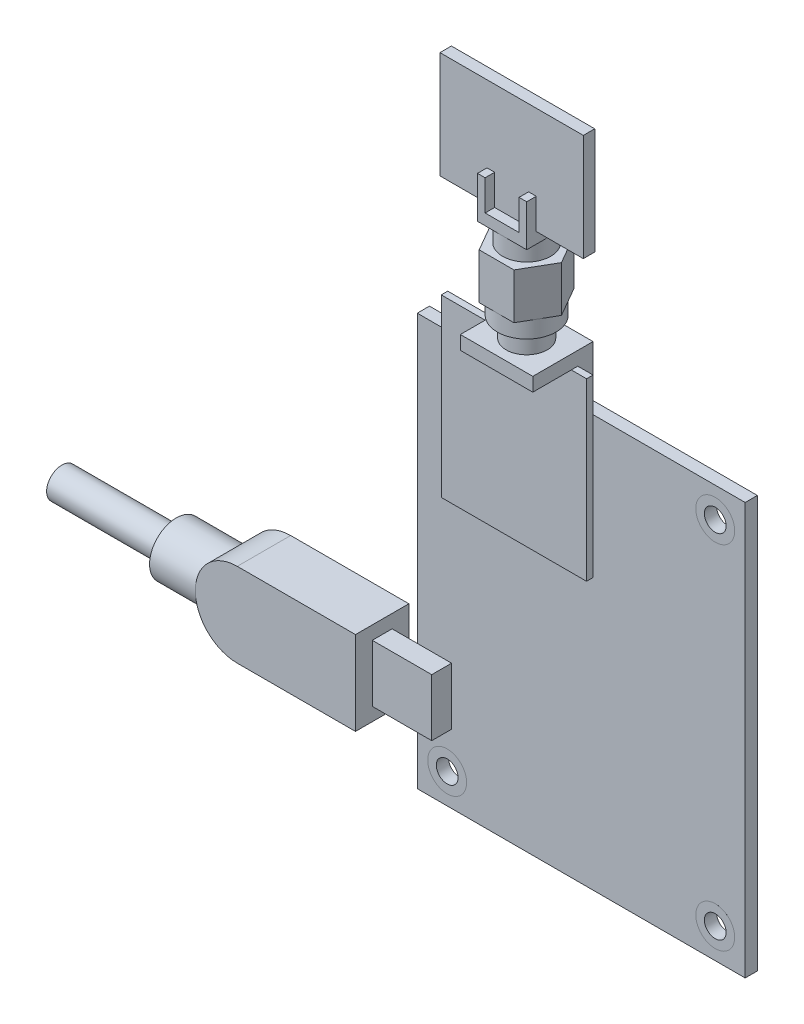
SolidWorks part; units mm, degrees
ref_plane "Front Plane" through (0, 0, 0) normal (0, 0, 1) x (1, 0, 0)
ref_plane "Top Plane" through (0, 0, 0) normal (0, 1, 0) x (1, 0, 0)
ref_plane "Right Plane" through (0, 0, 0) normal (1, 0, 0) x (0, 0, -1)
sketch "Sketch1" plane through (0, 0, 0) normal (0, 0, 1) x (1, 0, 0)
  line L1 (0, 0) -> (19.05, 0)
  line L2 (0, 0) -> (0, 23)
  line L3 (0, 23) -> (19.05, 23)
  line L4 (19.05, 0) -> (19.05, 23)
  dimension "D1" = 19.05
  dimension "D2" = 23
extrude "Blue PCB" add sketch "Sketch1" along normal mid plane 0.85
sketch "Sketch20" plane through (0, 0, -0.425) normal (0, 0, -1) x (-1, 0, 0)
  line L0 (-19.05, 23) -> (0, 23) construction
  line L1 (4, 18.5) -> (-39, 18.5)
  line L2 (4, 18.5) -> (4, -35.5)
  line L3 (4, -35.5) -> (-39, -35.5)
  line L4 (-39, 18.5) -> (-39, -35.5)
  line L5 (0, 23) -> (0, 0) construction
  dimension "D1" = 43
  dimension "D2" = 54
  dimension "D3" = 4.5
  dimension "D4" = 4
extrude "Green PCB" add sketch "Sketch20" along normal blind 1.6
ref_plane "Plane3" through (0, 0, -1.225) normal (0, 0, 1) x (1, 0, 0)
sketch "Sketch21" plane through (0, 0, -0.425) normal (0, 0, 1) x (1, 0, 0)
  line L0 (39, 18.5) -> (39, -35.5) construction
  line L1 (35.075, 14.575) -> (-0.075, 14.575) construction
  line L2 (35.075, 14.575) -> (35.075, -31.575) construction
  line L3 (35.075, -31.575) -> (-0.075, -31.575) construction
  line L4 (-0.075, 14.575) -> (-0.075, -31.575) construction
  line L5 (19.05, 18.5) -> (39, 18.5) construction
  line L6 (39, -35.5) -> (-4, -35.5) construction
  line L7 (-4, -35.5) -> (-4, 18.5) construction
  circle A0 centre (35.075, 14.575) radius 1.425
  circle A1 centre (35.075, -31.575) radius 1.425
  circle A2 centre (-0.075, -31.575) radius 1.425
  point P6 (33.5564, -31.4187)
  dimension "D1" = 2.85
  dimension "D2" = 3.925
  dimension "D3" = 3.925
  dimension "D4" = 3.925
  dimension "D5" = 3.925
extrude "Mounting Holes" cut sketch "Sketch21" against normal through all
sketch "Sketch22" plane through (0, 0, -1.225) normal (0, 0, 1) x (1, 0, 0)
  circle A0 centre (35.075, 14.575) radius 2.55
  circle A1 centre (35.075, -31.575) radius 2.55
  circle A2 centre (-0.075, -31.575) radius 2.55
  circle A3 centre (-0.075, -31.575) radius 1.425
  circle A4 centre (35.075, -31.575) radius 1.425
  circle A5 centre (35.075, 14.575) radius 1.425
  circle A6 centre (35.075, 14.575) radius 1.425 construction
  circle A7 centre (35.075, -31.575) radius 1.425 construction
  circle A8 centre (-0.075, -31.575) radius 1.425 construction
  dimension "D1" = 5.1
extrude "Screw Mask" add sketch "Sketch22" along normal offset from surface 0.001 and the other way offset from surface (0.801 mm away) 0.001 up to face at (36.5, 14.575, -0.425) offset beyond the face yes other way up to face at (36.5, 14.575, -2.025)
sketch "Sketch4" plane through (0, 23, 0) normal (0, 1, 0) x (1, 0, 0)
  line L0 (19.05, -0.425) -> (19.05, 0.425) construction
  line L1 (7.55, 2.425) -> (17.05, 2.425)
  line L2 (7.55, 2.425) -> (7.55, -5.475)
  line L3 (7.55, -5.475) -> (17.05, -5.475)
  line L4 (17.05, 2.425) -> (17.05, -5.475)
  line L6 (19.05, 0.425) -> (0, 0.425) construction
  dimension "D1" = 7.9
  dimension "D2" = 9.5
  dimension "D3" = 2
  dimension "D4" = 2
extrude "Antenna1" add sketch "Sketch4" along normal blind 1.8
sketch "Sketch10" plane through (0, 0, -2.425) normal (0, 0, 1) x (1, 0, 0)
  line L1 (7.55, 23) -> (8.8, 23)
  line L2 (7.55, 23) -> (7.55, 18.5)
  line L3 (7.55, 18.5) -> (8.8, 18.5)
  line L4 (8.8, 23) -> (8.8, 18.5)
  line L5 (17.05, 23) -> (15.8, 23)
  line L6 (17.05, 23) -> (17.05, 18.5)
  line L7 (17.05, 18.5) -> (15.8, 18.5)
  line L8 (15.8, 23) -> (15.8, 18.5)
  dimension "D1" = 1.25
  dimension "D2" = 4.5
extrude "Antenna2" add sketch "Sketch10" against normal up to surface (2.85 mm away)
sketch "Sketch5" plane through (0, 24.8, 0) normal (0, 1, 0) x (1, 0, 0)
  line L0 (17.05, 2.425) -> (7.55, -5.475) construction
  circle A0 centre (12.3, -1.525) radius 2.7
  dimension "D1" = 5.4
extrude "Antenna3" add sketch "Sketch5" along normal blind 2.6
sketch "Sketch6" plane through (0, 27.4, 0) normal (0, 1, 0) x (1, 0, 0)
  circle A0 centre (12.3, -1.525) radius 3.85
  dimension "D1" = 7.7
extrude "Antenna4" add sketch "Sketch6" along normal blind 2.25
sketch "Sketch7" plane through (0, 29.65, 0) normal (0, 1, 0) x (1, 0, 0)
  line L0 (7.55, -5.475) -> (17.05, -5.475) construction
  line L1 (10.0195, -5.475) -> (14.5805, -5.475)
  line L2 (14.5805, -5.475) -> (16.8611, -1.525)
  line L3 (16.8611, -1.525) -> (14.5805, 2.425)
  line L4 (14.5805, 2.425) -> (10.0195, 2.425)
  line L5 (10.0195, 2.425) -> (7.7389, -1.525)
  line L6 (7.7389, -1.525) -> (10.0195, -5.475)
  circle A0 centre (12.3, -1.525) radius 3.95 construction
  dimension "D1" = 7.9
extrude "Antenna5" add sketch "Sketch7" along normal blind 6
sketch "Sketch8" plane through (0, 35.65, 0) normal (0, 1, 0) x (1, 0, 0)
  circle A0 centre (12.3, -1.525) radius 3.15
  dimension "D1" = 6.3
extrude "Antenna6" add sketch "Sketch8" along normal blind 2.4
sketch "Sketch9" plane through (0, 38.05, 0) normal (0, 1, 0) x (1, 0, 0)
  line L1 (15.525, 1.7) -> (9.075, 1.7)
  line L2 (15.525, 1.7) -> (15.525, -4.75)
  line L3 (15.525, -4.75) -> (9.075, -4.75)
  line L4 (9.075, 1.7) -> (9.075, -4.75)
  line L5 (15.525, 1.7) -> (9.075, -4.75) construction
  line L6 (15.525, -4.75) -> (9.075, 1.7) construction
  point P0 (12.3, -1.525)
  dimension "D1" = 6.45
  dimension "D2" = 6.45
extrude "Antenna7" add sketch "Sketch9" along normal blind 1.45
sketch "Sketch19" plane through (0, 0, 4.75) normal (0, 0, 1) x (1, 0, 0)
  line L0 (9.075, 39.5) -> (9.075, 38.05) construction
  line L1 (9.075, 39.5) -> (10.075, 39.5)
  line L2 (9.075, 39.5) -> (9.075, 43.5)
  line L3 (9.075, 43.5) -> (10.075, 43.5)
  line L4 (10.075, 39.5) -> (10.075, 43.5)
  line L5 (9.075, 39.5) -> (15.525, 39.5) construction
  line L7 (15.525, 39.5) -> (14.525, 39.5)
  line L8 (15.525, 39.5) -> (15.525, 43.5)
  line L9 (15.525, 43.5) -> (14.525, 43.5)
  line L10 (14.525, 39.5) -> (14.525, 43.5)
  dimension "D1" = 1
  dimension "D2" = 4
extrude "Antenna8" add sketch "Sketch19" against normal blind 1.25
sketch "Sketch11" plane through (0, 39.5, 0) normal (0, 1, 0) x (1, 0, 0)
  line L0 (14.525, -3.5) -> (15.525, -3.5) construction
  line L1 (21.7, -2) -> (2.9, -2)
  line L2 (21.7, -2) -> (21.7, -3.5)
  line L3 (21.7, -3.5) -> (2.9, -3.5)
  line L4 (2.9, -2) -> (2.9, -3.5)
  line L6 (12.3, 1.7) -> (12.3, -4.75) construction
  line L7 (15.525, 1.7) -> (9.075, 1.7) construction
  line L8 (10.075, -4.75) -> (14.525, -4.75) construction
  point P6 (0.3478, -3.5)
  point P7 (12.3, -2)
  dimension "D1" = 18.8
  dimension "D2" = 1.5
extrude "Antenna PCB" add sketch "Sketch11" along normal blind 14
sketch "Sketch14" plane through (0, 0, -0.425) normal (0, 0, -1) x (-1, 0, 0)
  line L1 (-0.5, -19) -> (7.3, -19)
  line L2 (-0.5, -19) -> (-0.5, -26.5)
  line L3 (-0.5, -26.5) -> (7.3, -26.5)
  line L4 (7.3, -19) -> (7.3, -26.5)
  line L5 (-39, -35.5) -> (4, -35.5) construction
  line L7 (4, -35.5) -> (4, 18.5) construction
  dimension "D1" = 7.5
  dimension "D2" = 7.8
  dimension "D3" = 9
  dimension "D4" = 4.5
extrude "USB Port" add sketch "Sketch14" against normal blind 2.6
ref_plane "Plane1" through (0, 0, 0.875) normal (0, 0, 1) x (1, 0, 0)
sketch "Sketch16" plane through (0, 0, 0.875) normal (0, 0, 1) x (1, 0, 0)
  line L0 (-22.8, -28.25) -> (-7.3, -28.25)
  line L1 (-7.3, -28.25) -> (-7.3, -17.25)
  line L2 (-7.3, -17.25) -> (-22.8, -17.25)
  line L3 (-7.3, -19) -> (-7.3, -26.5) construction
  arc A1 (-22.8, -28.25) -> (-22.8, -17.25) centre (-22.8, -22.75) ccw construction
  arc A2 (-22.8, -17.25) -> (-22.8, -28.25) centre (-22.8, -22.75) ccw
  point P7 (-7.3, -22.75)
  dimension "D1" = 11
  dimension "D2" = 21
extrude "USB Body" add sketch "Sketch16" along normal mid plane 7
ref_plane "Plane2" through (-28.3, 0, 0) normal (-1, 0, 0) x (0, 0, 1)
sketch "Sketch17" plane through (-28.3, 0, 0) normal (-1, 0, 0) x (0, 0, 1)
  line L0 (4.375, -28.25) -> (4.375, -17.25) construction
  line L2 (-2.625, -22.75) -> (4.375, -22.75) construction
  line L3 (-2.625, -17.25) -> (-2.625, -28.25) construction
  circle A0 centre (0.875, -22.75) radius 3.5
  point P4 (4.375, -22.75)
  point P12 (0.875, -22.75)
  point P16 (-2.625, -22.75)
extrude "USB Tension Relief" add sketch "Sketch17" along normal blind 6 and the other way up to surface (6 mm away)
sketch "Sketch18" plane through (-34.3, 0, 0) normal (-1, 0, 0) x (0, 0, 1)
  circle A0 centre (0.875, -22.75) radius 2
  dimension "D1" = 4
extrude "USB Cord" add sketch "Sketch18" along normal blind 15
ref_plane "Plane4" through (0, 0, 2.75) normal (0, 0, -1) x (-1, 0, 0)
mirror "Mirror1" about plane through (0, 0, 2.75) normal (0, 0, -1) of "Antenna8"
